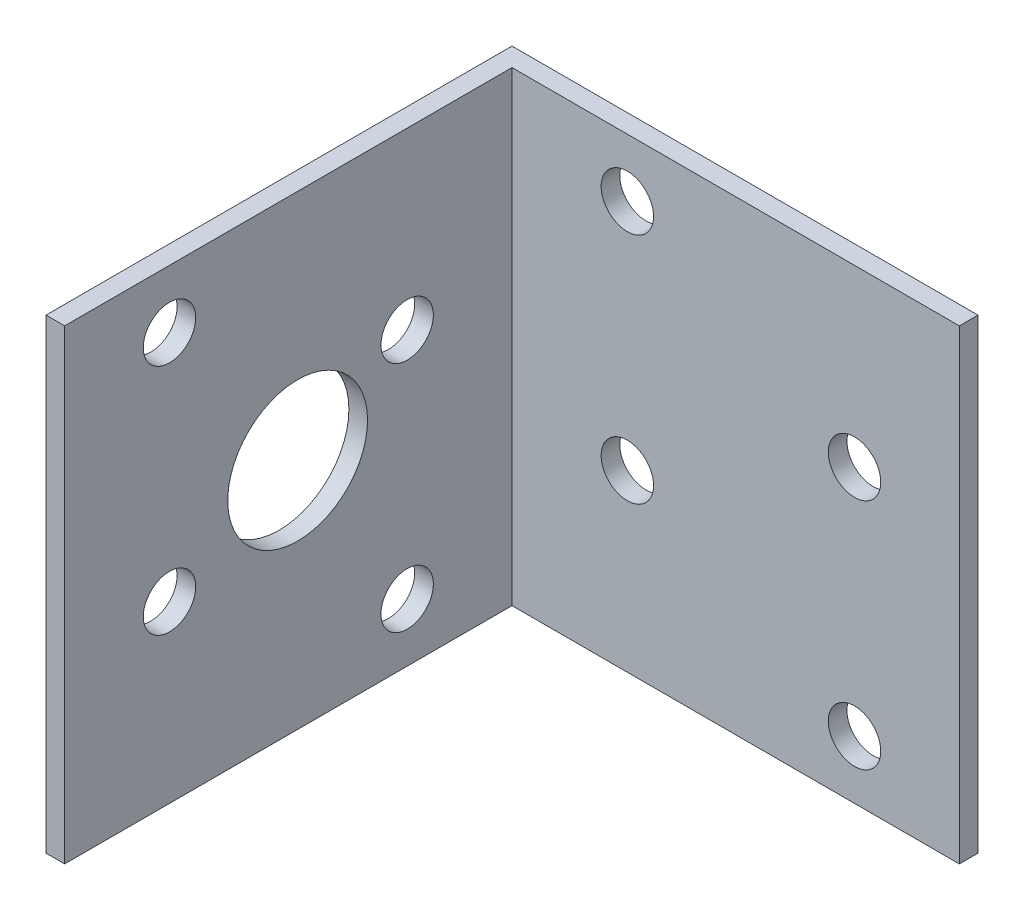
SolidWorks part; units mm, degrees
material "Хромированная нержавеющая сталь"
ref_plane "Спереди" through (0, 0, 0) normal (0, 0, 1) x (1, 0, 0)
ref_plane "Сверху" through (0, 0, 0) normal (0, 1, 0) x (1, 0, 0)
ref_plane "Справа" through (0, 0, 0) normal (1, 0, 0) x (0, 0, -1)
ref_plane "Плоскость4" through (40, 0, 0) normal (1, 0, 0) x (0, 0, -1)
sketch "Эскиз1" plane through (40, 0, 0) normal (1, 0, 0) x (0, 0, -1)
  line L0 (0, -40) -> (0, 0)
  line L1 (0, 0) -> (-40, 0)
  line L2 (-40, 0) -> (-40, -40)
  line L3 (-40, -40) -> (0, -40)
extrude "Бобышка-Вытянуть1" add sketch "Эскиз1" against normal blind 40
sketch "Эскиз2" plane through (0, 0, 0) normal (0, 1, 0) x (-1, 0, 0)
  line L0 (-1.6, 1.6) -> (-1.6, 40)
  line L1 (-1.6, 40) -> (-40, 40)
  line L2 (-40, 40) -> (-40, 1.6)
  line L3 (-40, 1.6) -> (-1.6, 1.6)
extrude "Вырез-Вытянуть1" cut sketch "Эскиз2" against normal through all
hole_wizard "Диаметр отверстия Ø4.5 (4.5)1" positions "Эскиз4" profile "Эскиз3" hole size "Ø4.5" standard "Ansi Metric"
sketch "Эскиз4" plane through (0, 0, 1.6) normal (0, 0, 1) x (1, 0, 0)
  point P0 (31, -15)
  point P1 (11.5, -5)
  point P2 (11.5, -25)
  point P3 (31, -35)
sketch "Эскиз3" plane through (31, -15, 1.6) normal (1, 0, 0) x (0, -1, 0)
  line L0 (0, 0) -> (0, 1.6)
  line L1 (0, 1.6) -> (2.25, 1.6)
  line L2 (2.25, 1.6) -> (2.25, 0)
  line L5 (2.25, 0) -> (0, 0)
  line L11 (0, -6.35) -> (0, 107.95) construction
  dimension "Диаметр сквозного отверстия" = 4.5
  dimension "Глубина сквозного отверстия" = 1.6
hole_wizard "Диаметр отверстия Ø12.0 (12)1" positions "Эскиз6" profile "Эскиз5" hole size "Ø12.0" standard "Ansi Metric"
sketch "Эскиз6" plane through (1.6, 0, 0) normal (1, 0, 0) x (0, 0, -1)
  point P0 (-20, -20)
sketch "Эскиз5" plane through (1.6, -20, 20) normal (0, 1, 0) x (0, 0, -1)
  line L0 (0, 0) -> (0, 1.6)
  line L1 (0, 1.6) -> (6, 1.6)
  line L2 (6, 1.6) -> (6, 0)
  line L5 (6, 0) -> (0, 0)
  line L11 (0, -6.35) -> (0, 107.95) construction
  dimension "Диаметр сквозного отверстия" = 12
  dimension "Глубина сквозного отверстия" = 1.6
hole_wizard "Диаметр отверстия Ø4.5 (4.5)2" positions "Эскиз8" profile "Эскиз7" hole size "Ø4.5" standard "Ansi Metric"
sketch "Эскиз8" plane through (1.6, 0, 0) normal (1, 0, 0) x (0, 0, -1)
  point P0 (-31, -25)
  point P1 (-10.6, -15)
  point P2 (-10.6, -35)
  point P3 (-31, -5)
sketch "Эскиз7" plane through (1.6, -25, 31) normal (0, 1, 0) x (0, 0, -1)
  line L0 (0, 0) -> (0, 1.6)
  line L1 (0, 1.6) -> (2.25, 1.6)
  line L2 (2.25, 1.6) -> (2.25, 0)
  line L5 (2.25, 0) -> (0, 0)
  line L11 (0, -6.35) -> (0, 107.95) construction
  dimension "Диаметр сквозного отверстия" = 4.5
  dimension "Глубина сквозного отверстия" = 1.6
